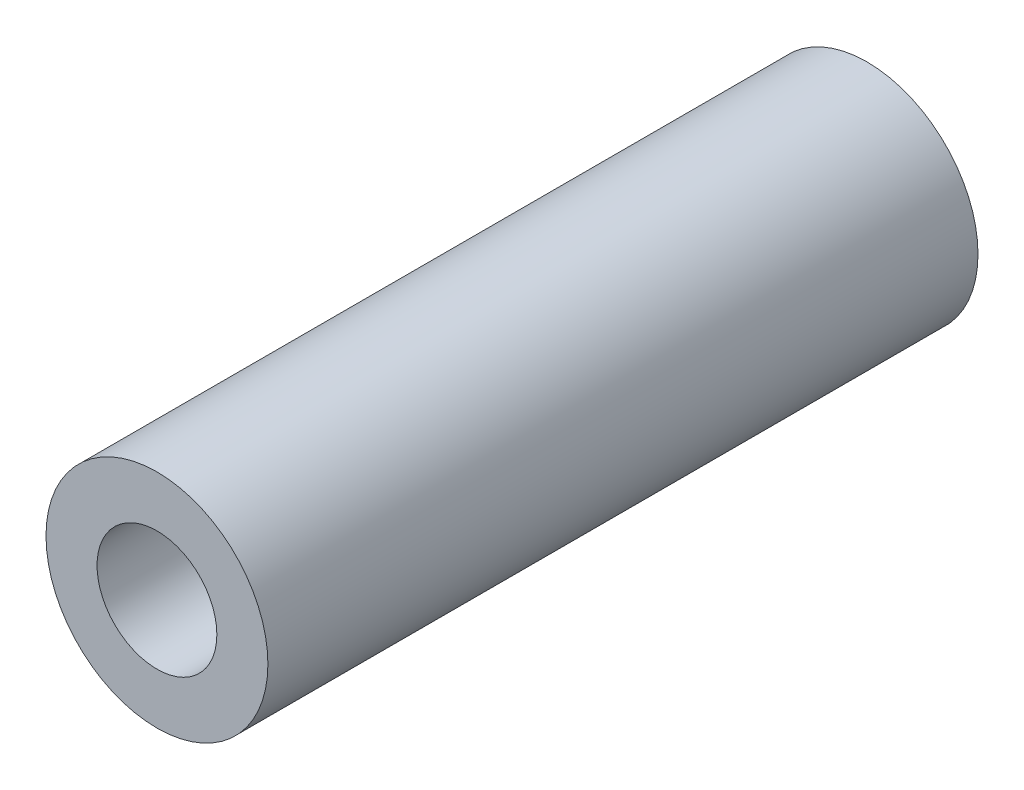
SolidWorks part; units mm, degrees
ref_plane "Alzado" through (0, 0, 0) normal (0, 0, 1) x (1, 0, 0)
ref_plane "Planta" through (0, 0, 0) normal (0, 1, 0) x (1, 0, 0)
ref_plane "Vista lateral" through (0, 0, 0) normal (1, 0, 0) x (0, 0, -1)
sketch "Croquis1" plane through (0, 0, 0) normal (0, 0, 1) x (1, 0, 0)
  circle A0 centre (0, 0) radius 2.5
  dimension "D1" = 5
extrude "Saliente-Extruir1" add sketch "Croquis1" along normal blind 16
sketch "Croquis2" plane through (0, 0, 16) normal (0, 0, 1) x (1, 0, 0)
  line L0 (0, 2.5) -> (0, -2.5) construction
  line L1 (-2.5, 0) -> (2.5, 0) construction
  circle A0 centre (0, 0) radius 2.5 construction
hole_wizard "Taladro de margen para M2.51" positions "Croquis5" profile "Croquis3" hole size "M2.5" standard "ISO" end condition through all
sketch "Croquis5" plane through (0, 0, 16) normal (0, 0, 1) x (1, 0, 0)
  point P0 (0, 0)
sketch "Croquis3" plane through (0, 0, 16) normal (1, 0, 0) x (0, -1, 0)
  line L0 (0, 0) -> (0, 16)
  line L1 (0, 16) -> (1.35, 16)
  line L2 (1.35, 16) -> (1.35, 0)
  line L5 (1.35, 0) -> (0, 0)
  line L11 (0, -6.35) -> (0, 107.95) construction
  dimension "Diámetro de taladro hasta el siguiente" = 2.7
  dimension "Profundidad de taladro hasta el siguiente" = 16
